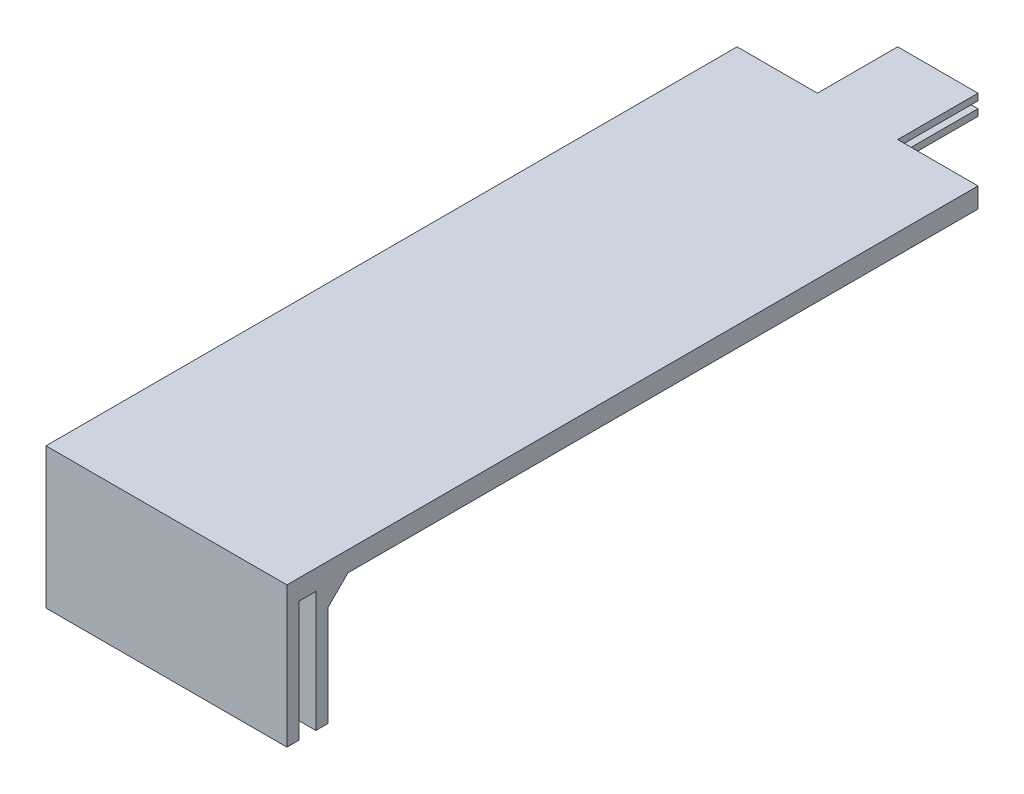
SolidWorks part; units mm, degrees
ref_plane "Front Plane" through (0, 0, 0) normal (0, 0, 1) x (1, 0, 0)
ref_plane "Top Plane" through (0, 0, 0) normal (0, 1, 0) x (1, 0, 0)
ref_plane "Right Plane" through (0, 0, 0) normal (1, 0, 0) x (0, 0, -1)
sketch "Sketch1" plane through (0, 0, 0) normal (0, 1, 0) x (1, 0, 0)
  line L1 (0, 0) -> (20, 0)
  line L2 (0, 0) -> (0, 80)
  line L3 (0, 80) -> (20, 80)
  line L4 (20, 0) -> (20, 80)
  dimension "D1" = 80
  dimension "D2" = 20
extrude "Boss-Extrude1" add sketch "Sketch1" along normal blind 5
sketch "Sketch2" plane through (0, 0, 0) normal (0, -1, 0) x (1, 0, 0)
  line L1 (20, 0) -> (0, 0)
  line L2 (20, 0) -> (20, 10.2)
  line L3 (20, 10.2) -> (0, 10.2)
  line L4 (0, 0) -> (0, 10.2)
  line L5 (0, -80) -> (0, 0) construction
  dimension "D1" = 10.2
  dimension "D2" = 0
extrude "Boss-Extrude2" add sketch "Sketch2" along normal blind 30 and the other way blind 5
sketch "Sketch3" plane through (0, -30, 0) normal (0, -1, 0) x (1, 0, 0)
  line L0 (20, 0) -> (20, 10.2) construction
  line L1 (20, 7.2) -> (0, 7.2)
  line L2 (20, 7.2) -> (20, 3)
  line L3 (20, 3) -> (0, 3)
  line L4 (0, 7.2) -> (0, 3)
  line L5 (0, 10.2) -> (0, 0) construction
  line L6 (0, 0) -> (20, 0) construction
  dimension "D1" = 4.2
  dimension "D2" = 3
extrude "Cut-Extrude1" cut sketch "Sketch3" against normal blind 30
sketch "Sketch5" plane through (0, 0, 0) normal (-1, 0, 0) x (0, 0, 1)
  line L0 (-80, 5) -> (10.2, 5) construction
  line L1 (10.2, -30) -> (7.2, -30)
  line L2 (10.2, -30) -> (10.2, 5)
  line L3 (10.2, 5) -> (7.2, 5)
  line L4 (7.2, -30) -> (7.2, 5)
  line L5 (7.2, 0) -> (7.2, -30) construction
  line M5 (0, -30) -> (3, -30)
  line M6 (3, -30) -> (3, 0)
  line M7 (3, 0) -> (7.2, 0)
  line M8 (7.2, 0) -> (7.2, -30)
  line M9 (7.2, -30) -> (10.2, -30)
  line M10 (10.2, -30) -> (10.2, 5)
  line M11 (10.2, 5) -> (-80, 5)
  line M12 (-80, 5) -> (-80, 0)
  line M13 (-80, 0) -> (0, 0)
  line M14 (0, 0) -> (0, -30)
extrude "Boss-Extrude3" add sketch "Sketch5" along normal blind 40 contours L4 M7 M11 M12 M13 M14 M5 M6 | L4 M8 M9 M10 M11
sketch "Sketch6" plane through (0, 0, -80) normal (0, 0, -1) x (-1, 0, 0)
  line L1 (-20, 0) -> (40, 0)
  line L2 (-20, 0) -> (-20, 5)
  line L3 (-20, 5) -> (40, 5)
  line L4 (40, 0) -> (40, 5)
extrude "Boss-Extrude4" add sketch "Sketch6" along normal blind 81.9
sketch "Sketch7" plane through (0, 0, -161.9) normal (0, 0, -1) x (-1, 0, 0)
  line L0 (-20, 0) -> (40, 0) construction
  line L1 (0, 0) -> (20, 0)
  line L2 (0, 0) -> (0, 5)
  line L3 (0, 5) -> (20, 5)
  line L4 (20, 0) -> (20, 5)
  line L5 (40, 5) -> (-20, 5) construction
  line L6 (40, 0) -> (40, 5) construction
  line L9 (0, 5) -> (20, 5)
  line L10 (0, 5) -> (0, 3.35)
  line L11 (0, 3.35) -> (20, 3.35)
  line L12 (20, 5) -> (20, 3.35)
  line L13 (20, 0) -> (0, 0)
  line L14 (20, 0) -> (20, 1.65)
  line L15 (20, 1.65) -> (0, 1.65)
  line L16 (0, 0) -> (0, 1.65)
  line M14 (-20, 0) -> (40, 0)
  line M16 (40, 5) -> (-20, 5)
  dimension "D1" = 20
  dimension "D2" = 20
  dimension "D3" = 1.7
  dimension "D4" = 1.65
extrude "Boss-Extrude5" add sketch "Sketch7" along normal blind 20 contours L2 L11 L4 M16 | L4 L15 L2 M14
chamfer "Chamfer1" distance 5 angle 45 1 edges at (-10, 0, 0)
